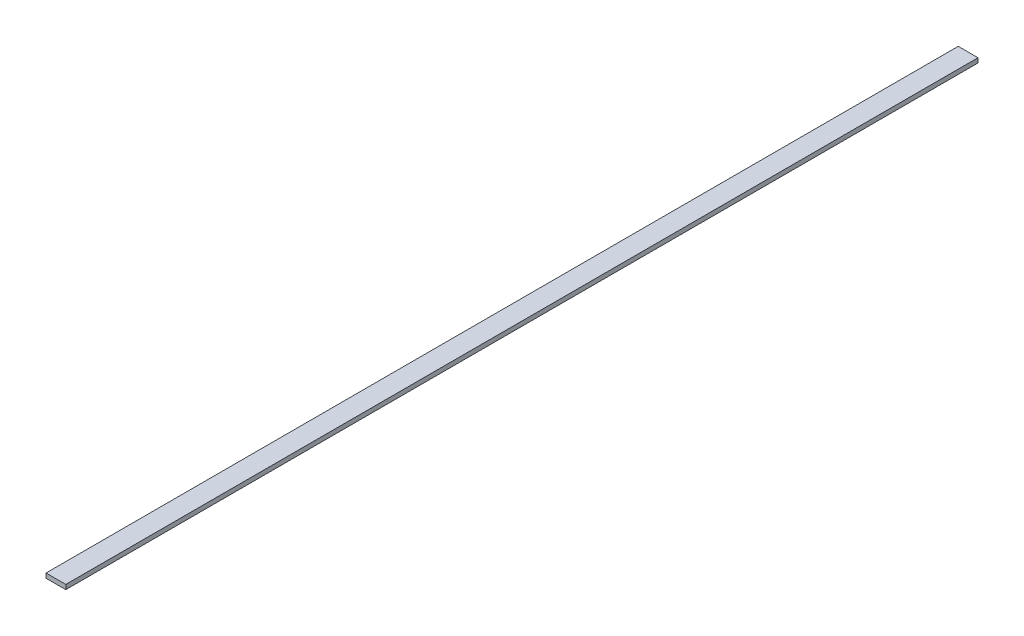
SolidWorks part; units mm, degrees
material "Borracha de silicone"
ref_plane "Plano frontal" through (0, 0, 0) normal (0, 0, 1) x (1, 0, 0)
ref_plane "Plano superior" through (0, 0, 0) normal (0, 1, 0) x (1, 0, 0)
ref_plane "Plano direito" through (0, 0, 0) normal (1, 0, 0) x (0, 0, -1)
sketch "Esboço1" plane through (0, 0, 0) normal (0, 0, 1) x (1, 0, 0)
  line L1 (-3.25, 0.75) -> (3.25, 0.75)
  line L2 (-3.25, 0.75) -> (-3.25, -0.75)
  line L3 (-3.25, -0.75) -> (3.25, -0.75)
  line L4 (3.25, 0.75) -> (3.25, -0.75)
  line L5 (-3.25, 0.75) -> (3.25, -0.75) construction
  line L6 (-3.25, -0.75) -> (3.25, 0.75) construction
  point P0 (0, 0)
  dimension "D1" = 6.5
  dimension "D2" = 1.5
extrude "Ressalto-extrusão1" add sketch "Esboço1" along normal blind 300
